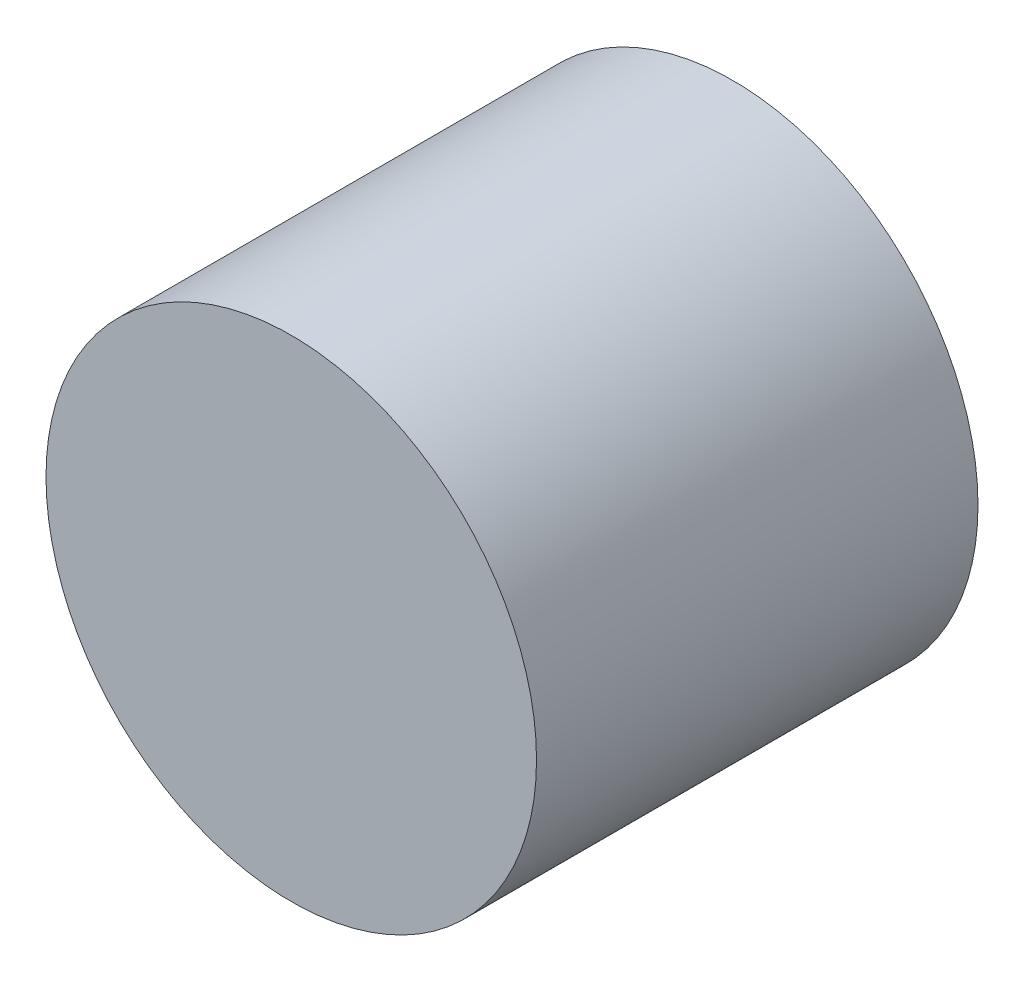
SolidWorks part; units mm, degrees
material "Акрил (Средняя-высокая ударопрочность)"
ref_plane "Спереди" through (0, 0, 0) normal (0, 0, 1) x (1, 0, 0)
ref_plane "Сверху" through (0, 0, 0) normal (0, 1, 0) x (1, 0, 0)
ref_plane "Справа" through (0, 0, 0) normal (1, 0, 0) x (0, 0, -1)
sketch "Эскиз1" plane through (0, 0, 0) normal (1, 0, 0) x (0, 0, -1)
  line L0 (-9.9162, 0) -> (12.2525, 0) construction
  line L1 (0, 10.9132) -> (0, -3.2392) construction
  line L2 (0, 0) -> (0, 5)
  line L3 (0, 5) -> (9, 5)
  line L4 (9, 5) -> (9, 3)
  line L5 (9, 3) -> (3.5, 3)
  line L6 (3.5, 3) -> (3.5, 4.5)
  line L7 (1.5, 0) -> (1.5, -2.9438) construction
  line L8 (0, 0) -> (1.5, 0)
  arc A0 (1.5, 0) -> (3.5, 4.5) centre (7.5625, 0) cw
  dimension "D1" = 9
  dimension "D2" = 5
  dimension "D3" = 1.5
  dimension "D4" = 5.5
  dimension "D5" = 3
  dimension "D6" = 1.5
revolve "Повернуть1" add sketch "Эскиз1" angle 360 about L0
